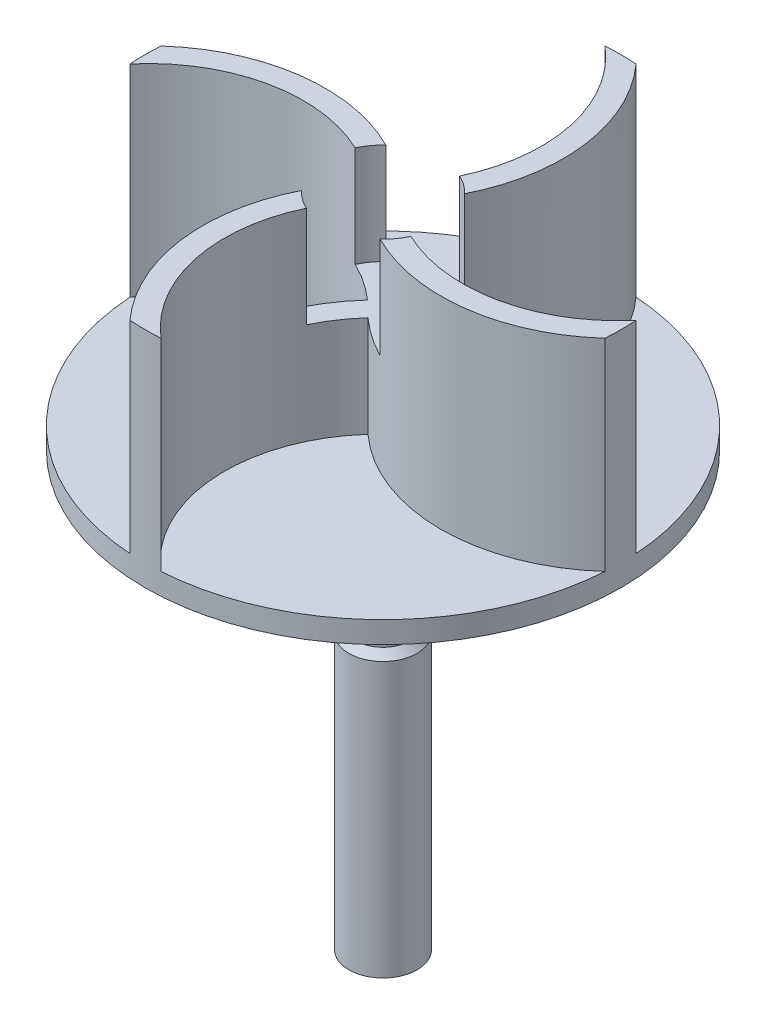
SolidWorks part; units mm, degrees
ref_plane "Front Plane" through (0, 0, 0) normal (0, 0, 1) x (1, 0, 0)
ref_plane "Top Plane" through (0, 0, 0) normal (0, 1, 0) x (1, 0, 0)
ref_plane "Right Plane" through (0, 0, 0) normal (1, 0, 0) x (0, 0, -1)
sketch "Sketch1" plane through (0, 0, 0) normal (0, 1, 0) x (1, 0, 0)
  circle A0 centre (0, 0) radius 33
  dimension "D1" = 66
extrude "Boss-Extrude1" add sketch "Sketch1" along normal blind 3
sketch "Sketch3" plane through (0, 3, 0) normal (0, 1, 0) x (1, 0, 0)
  line L0 (-1.0761, -1.045) -> (1.0761, 1.045)
  arc A0 (0, 0) -> (33, 0) centre (16.5, 16.0234) ccw construction
  circle A1 centre (0, 0) radius 33 construction
  arc A2 (-1.0761, -1.045) -> (32.9298, -2.151) centre (16.5, 16.0234) ccw
  arc A3 (1.0761, 1.045) -> (32.9295, 2.1555) centre (16.5, 16.0234) ccw
  arc A4 (-1.0761, -1.045) -> (34.0761, -1.045) centre (16.5, 16.0234) ccw construction
  arc A5 (1.0761, 1.045) -> (31.9239, 1.045) centre (16.5, 16.0234) ccw construction
  arc A6 (32.9295, 2.1555) -> (32.9298, -2.151) centre (0, 0) cw
  circle M2 centre (0, 0) radius 33
  dimension "D1" = 23
  dimension "D2" = 16.5
  dimension "D3" = 1.5
  dimension "D4" = 1.5
extrude "Boss-Extrude3" add sketch "Sketch3" along normal blind 28 contours A3 L0 A2 M2
pattern_circular "CirPattern2" count 4 over 360 about axis through (0, 0, 0) along (0, 1, 0) of "Boss-Extrude3"
sketch "Sketch4" plane through (0, 31, 0) normal (0, 1, 0) x (1, 0, 0)
  circle A0 centre (0, 0) radius 8
  dimension "D1" = 16
extrude "Cut-Extrude1" cut sketch "Sketch4" against normal blind 14
sketch "Sketch5" plane through (0, 0, 0) normal (0, -1, 0) x (1, 0, 0)
  circle A0 centre (0, 0) radius 4.75
  dimension "D1" = 9.5
extrude "Boss-Extrude4" add sketch "Sketch5" along normal blind 60
sketch "Sketch6" plane through (0, 0, 0) normal (0, 0, 1) x (1, 0, 0)
  line L0 (-4.75, -16) -> (-3.75, -17)
  line L1 (-4.75, 0) -> (-4.75, -60) construction
  line L2 (-3.75, -17) -> (-3.75, -21)
  line L3 (-3.75, -21) -> (-4.75, -22)
  line L4 (-4.75, -22) -> (-4.75, -16)
  line L5 (-33, 0) -> (33, 0) construction
  line L6 (0, 0) -> (0, -60) construction
  line L7 (-4.75, -60) -> (4.75, -60) construction
  dimension "D1" = 22
  dimension "D2" = 6
  dimension "D3" = 1
  dimension "D4" = 45
revolve "Cut-Revolve1" cut sketch "Sketch6" angle 360 about L6
